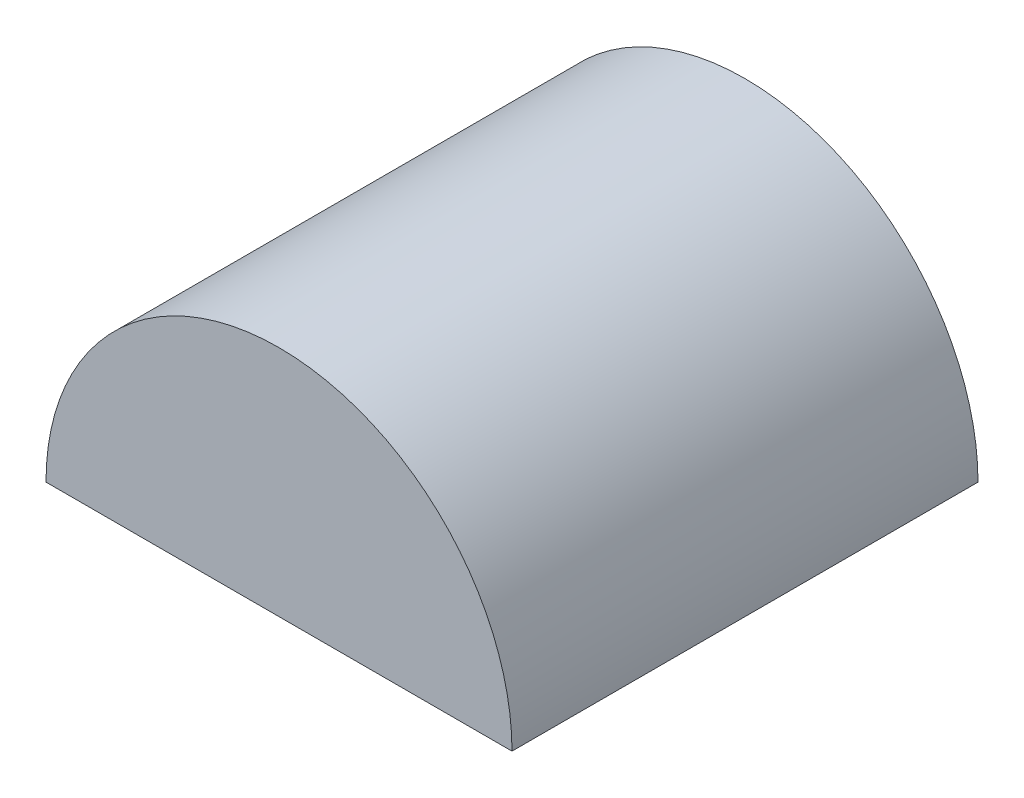
SolidWorks part; units mm, degrees
ref_plane "Front Plane" through (0, 0, 0) normal (0, 0, 1) x (1, 0, 0)
ref_plane "Top Plane" through (0, 0, 0) normal (0, 1, 0) x (1, 0, 0)
ref_plane "Right Plane" through (0, 0, 0) normal (1, 0, 0) x (0, 0, -1)
sketch "Sketch1" plane through (0, 0, 0) normal (0, 0, 1) x (1, 0, 0)
  line L0 (0, 0) -> (-0.25, 0)
  line L1 (0, 0) -> (0.25, 0)
  arc A0 (-0.25, 0) -> (0.25, 0) centre (0, 0) cw
  dimension "D1" = 0.25
extrude "Boss-Extrude1" add sketch "Sketch1" along normal blind 0.5
equation "\"t\"= 0.25'thickness of the sheets"
equation "\"t_cf\" = 0.115'thickness of single carbon fiber layer"
equation "\"t_kapton\" = 0.025'thickness of single Kapton flex layer"
equation "\"t_fr4\" = 0.1'thickness of FR4 with copper layer"
equation "\"joint_flex\"= 0.1'Width of flextures gap"
equation "\"joint_flex_eff\"= 0.02'Width of flecture after castelation"
equation "\"joint_fold\"= 0.2'Width of folding joints for 90deg fold"
equation "\"gap_tolerance\"= 0.002'Width to have interfecence fit between carbon fiber inserts"
equation "\"assemble_angle\"= 90'Angle of assembly parts"
equation "\"link_lift\"= 0.5'Actuation linkage amplification for the lift motion"
equation "\"link_swing\"= 0.45'Actuation linkage amplification for the swing motion"
equation "\"D1@Boss-Extrude1\"=\"joint_fold\""
equation "\"D1@Sketch1\"=\"t\""
